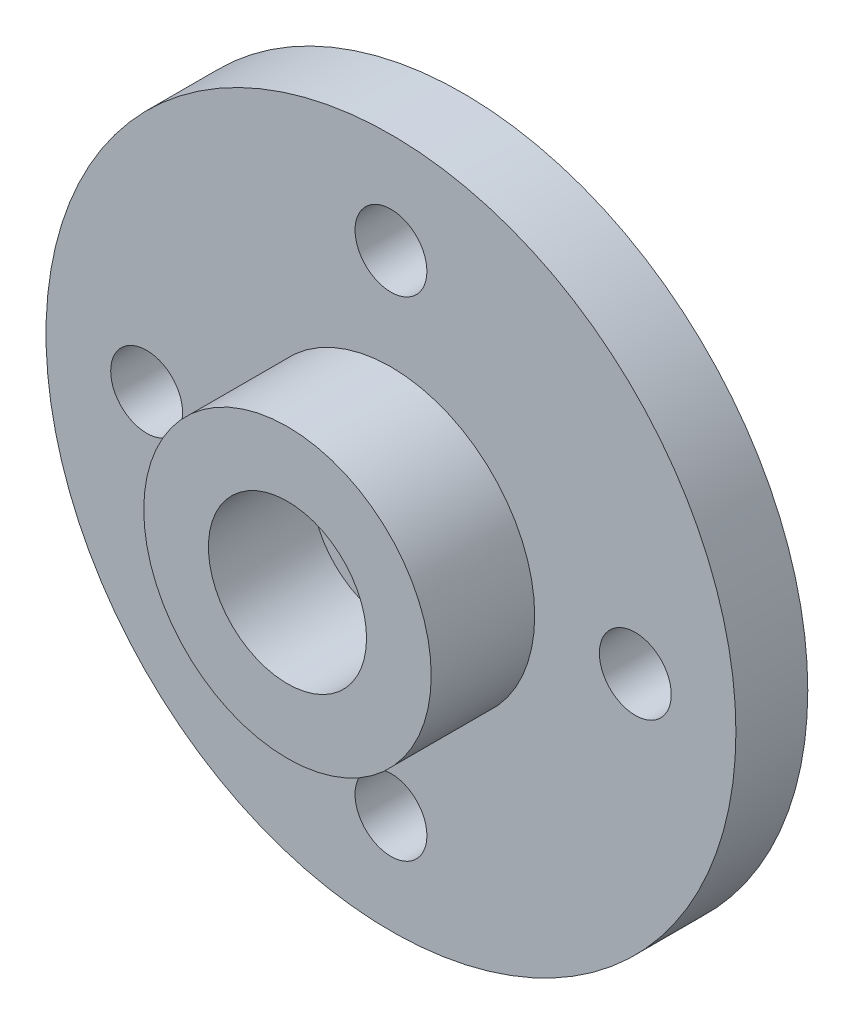
SolidWorks part; units mm, degrees
ref_plane "Plan de face" through (0, 0, 0) normal (0, 0, 1) x (1, 0, 0)
ref_plane "Plan de dessus" through (0, 0, 0) normal (0, 1, 0) x (1, 0, 0)
ref_plane "Plan de droite" through (0, 0, 0) normal (1, 0, 0) x (0, 0, -1)
sketch "Esquisse1" plane through (0, 0, 0) normal (0, 0, 1) x (1, 0, 0)
  circle A0 centre (0, 0) radius 12
  dimension "D1" = 24
extrude "Boss.-Extru.1" add sketch "Esquisse1" along normal blind 2.5
sketch "Esquisse2" plane through (0, 0, 2.5) normal (0, 0, 1) x (1, 0, 0)
  circle A0 centre (0, 0) radius 5
  circle A1 centre (0, 0) radius 2.75
  dimension "D1" = 10
  dimension "D2" = 5.5
extrude "Boss.-Extru.2" add sketch "Esquisse2" along normal blind 3.6
sketch "Esquisse3" plane through (0, 0, 0) normal (0, 0, -1) x (-1, 0, 0)
  circle A0 centre (0, 0) radius 1.4903
  circle A1 centre (0, 8.5) radius 1.25
  circle A2 centre (8.5, 0) radius 1.25
  circle A3 centre (0, -8.5) radius 1.25
  circle A4 centre (-8.5, 0) radius 1.25
  point P14 (0, 0)
  dimension "D1" = 2.5
  dimension "D2" = 8.5
  dimension "D3" = 4
extrude "Enlèv. mat.-Extru.1" cut sketch "Esquisse3" against normal through all
